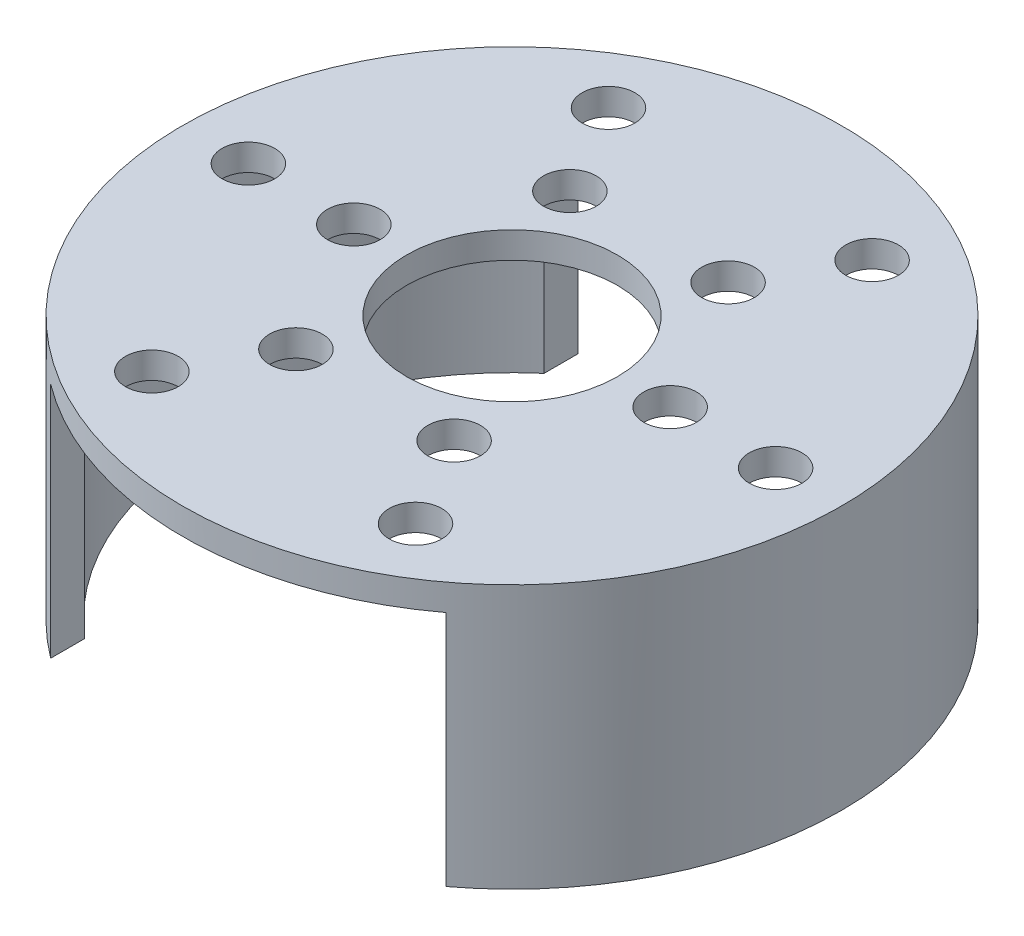
SolidWorks part; units mm, degrees
material "6061 Alloy"
ref_plane "Front Plane" through (0, 0, 0) normal (0, 0, 1) x (1, 0, 0)
ref_plane "Top Plane" through (0, 0, 0) normal (0, 1, 0) x (1, 0, 0)
ref_plane "Right Plane" through (0, 0, 0) normal (1, 0, 0) x (0, 0, -1)
sketch "Sketch1" plane through (0, 0, 0) normal (0, 1, 0) x (1, 0, 0)
  circle A0 centre (0, 0) radius 12.5
  dimension "D1" = 25
extrude "Boss-Extrude1" add sketch "Sketch1" along normal blind 10
shell "Shell1" thickness 1
sketch "Sketch2" plane through (0, 0, 0) normal (0, 0, 1) x (1, 0, 0)
  line L0 (0, 0) -> (0, 9) construction
  line L1 (12.5, 10) -> (-12.5, 10) construction
  line L2 (7.5, 9) -> (-7.5, 9)
  line L3 (-7.5, 9) -> (-7.5, 0)
  line L4 (-12.5, 0) -> (12.5, 0) construction
  line L5 (-12.5, 10) -> (-12.5, 0) construction
  line L6 (-7.5, 0) -> (7.5, 0)
  line L7 (7.5, 9) -> (7.5, 0)
  dimension "D1" = 1
  dimension "D2" = 5
extrude "Cut-Extrude1" cut sketch "Sketch2" against normal through all both and the other way through all
sketch "Sketch3" plane through (0, 10, 0) normal (0, 1, 0) x (1, 0, 0)
  line L0 (0, 0) -> (-10, 0) construction
  circle A19 centre (0, 0) radius 10 construction
  circle A20 centre (-10, 0) radius 1
  circle A21 centre (-6, 0) radius 1
  circle A22 centre (-5, 8.6603) radius 1
  circle A23 centre (-3, 5.1962) radius 1
  circle A24 centre (5, 8.6603) radius 1
  circle A25 centre (3, 5.1962) radius 1
  circle A26 centre (10, 0) radius 1
  circle A27 centre (6, 0) radius 1
  circle A28 centre (5, -8.6603) radius 1
  circle A29 centre (3, -5.1962) radius 1
  circle A30 centre (-5, -8.6603) radius 1
  circle A31 centre (-3, -5.1962) radius 1
  dimension "D1" = 20
  dimension "D2" = 2
  dimension "D3" = 2
  dimension "D4" = 6
  dimension "D5" = 6
extrude "Cut-Extrude2" cut sketch "Sketch3" against normal blind 10
sketch "Sketch4" plane through (0, 10, 0) normal (0, 1, 0) x (1, 0, 0)
  circle A0 centre (0, 0) radius 4
  dimension "D1" = 8
extrude "Cut-Extrude3" cut sketch "Sketch4" against normal blind 10
